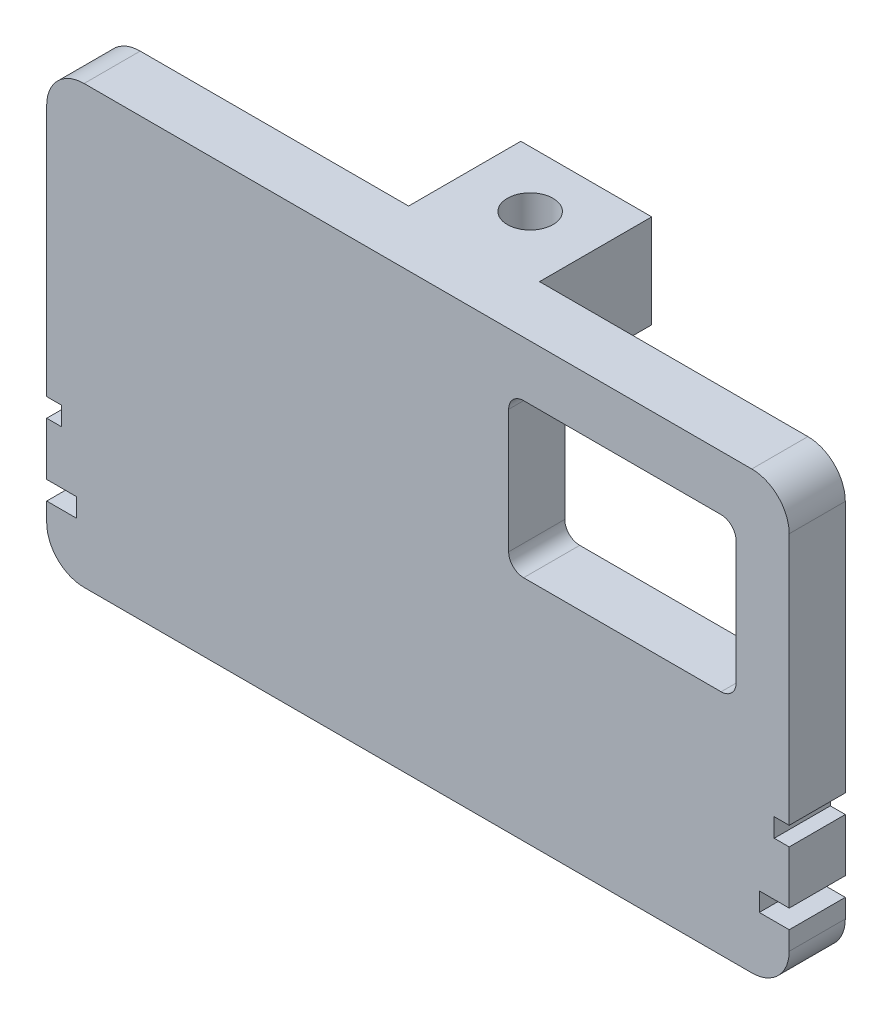
SolidWorks part; units mm, degrees
ref_plane "Front Plane" through (0, 0, 0) normal (0, 0, 1) x (1, 0, 0)
ref_plane "Top Plane" through (0, 0, 0) normal (0, 1, 0) x (1, 0, 0)
ref_plane "Right Plane" through (0, 0, 0) normal (1, 0, 0) x (0, 0, -1)
sketch "Sketch1" plane through (0, 0, 0) normal (0, 0, 1) x (1, 0, 0)
  line L0 (34.5888, 28.0084) -> (-10.7502, 28.0084) construction
  line L1 (34.5888, -1.6266) -> (-10.7502, -1.6266) construction
  line L2 (37.1288, 0.9134) -> (37.1288, 2.1834) construction
  line L3 (37.1288, 0.9134) -> (37.1288, 2.1834)
  line L4 (37.1288, 2.1834) -> (35.0968, 2.1834)
  line L5 (35.0968, 2.1834) -> (35.0968, 3.4534)
  line L6 (35.0968, 3.4534) -> (37.1288, 3.4534)
  line L7 (37.1288, 3.4534) -> (37.1288, 7.0534)
  line L8 (37.1288, 7.0534) -> (36.1128, 7.0534)
  line L9 (36.1128, 7.0534) -> (36.1128, 8.3234)
  line L10 (36.1128, 8.3234) -> (37.1288, 8.3234)
  line L11 (37.1288, 8.3234) -> (37.1288, 25.4684)
  line L12 (34.5888, -1.6266) -> (-10.7502, -1.6266)
  line L13 (-13.2902, 0.9134) -> (-13.2902, 2.1834)
  line L14 (-13.2902, 2.1834) -> (-11.2582, 2.1834)
  line L15 (-11.2582, 2.1834) -> (-11.2582, 3.4534)
  line L16 (-11.2582, 3.4534) -> (-13.2902, 3.4534)
  line L17 (-13.2902, 3.4534) -> (-13.2902, 7.0534) construction
  line L18 (-11.2582, 3.4534) -> (-13.2902, 3.4534) construction
  line L19 (-13.2902, 3.4534) -> (-13.2902, 7.0534)
  line L20 (-13.2902, 7.0534) -> (-12.2742, 7.0534)
  line L21 (-12.2742, 7.0534) -> (-12.2742, 8.3234)
  line L22 (-12.2742, 8.3234) -> (-13.2902, 8.3234)
  line L23 (-13.2902, 8.3234) -> (-13.2902, 25.4684)
  line L24 (-10.7502, 28.0084) -> (34.5888, 28.0084)
  line L25 (21.8888, 20.4696) -> (29.712, 20.4696) construction
  line L26 (32.506, 24.2796) -> (19.0948, 24.2796)
  line L27 (33.522, 23.2636) -> (33.522, 14.8816)
  line L28 (32.506, 13.8656) -> (19.0948, 13.8656)
  line L29 (18.0788, 23.2636) -> (18.0788, 14.8816)
  line L30 (21.8888, 17.6756) -> (29.712, 17.6756) construction
  line L31 (29.712, 20.4696) -> (29.712, 17.6756) construction
  line L32 (21.8888, 20.4696) -> (21.8888, 17.6756) construction
  arc A0 (-13.2902, 25.4684) -> (-10.7502, 28.0084) centre (-10.7502, 25.4684) cw
  arc A1 (34.5888, 28.0084) -> (37.1288, 25.4684) centre (34.5888, 25.4684) cw
  arc A2 (37.1288, 25.4684) -> (34.5888, 28.0084) centre (34.5888, 25.4684) ccw construction
  arc A3 (-13.2902, 0.9134) -> (-10.7502, -1.6266) centre (-10.7502, 0.9134) ccw
  arc A4 (34.5888, -1.6266) -> (37.1288, 0.9134) centre (34.5888, 0.9134) ccw
  arc A5 (19.0948, 13.8656) -> (18.0788, 14.8816) centre (19.0948, 14.8816) cw
  arc A6 (33.522, 14.8816) -> (32.506, 13.8656) centre (32.506, 14.8816) cw
  arc A7 (32.506, 24.2796) -> (33.522, 23.2636) centre (32.506, 23.2636) cw
  arc A8 (19.0948, 24.2796) -> (18.0788, 23.2636) centre (19.0948, 23.2636) ccw
  dimension "D5" = 1.016
  dimension "D1" = 3.81
  dimension "D2" = 3.81
  dimension "D3" = 3.81
  dimension "D4" = 3.81
extrude "Boss-Extrude1" add sketch "Sketch1" against normal blind 3.81
sketch "Sketch2" plane through (0, 0, -3.81) normal (0, 0, -1) x (-1, 0, 0)
  line L0 (-34.5888, 28.0084) -> (10.7502, 28.0084) construction
  line L2 (-16.3643, 28.0084) -> (-7.4743, 28.0084)
  line L3 (-16.3643, 28.0084) -> (-16.3643, 21.6584)
  line L4 (-16.3643, 21.6584) -> (-7.4743, 21.6584)
  line L5 (-7.4743, 28.0084) -> (-7.4743, 21.6584)
  point P0 (-11.9193, 28.0084)
  point P1 (-16.3643, 28.0084)
  dimension "D1" = 4.445
  dimension "D2" = 8.89
  dimension "D3" = 6.35
extrude "Boss-Extrude2" add sketch "Sketch2" along normal blind 7.62
sketch "Sketch3" plane through (0, 28.0084, 0) normal (0, 1, 0) x (1, 0, 0)
  line L0 (7.4743, 3.81) -> (16.3643, 11.43)
  circle A0 centre (11.9193, 7.62) radius 1.55
  dimension "D1" = 3.1
extrude "Cut-Extrude1" cut sketch "Sketch3" against normal blind 7.62 contours L0 A0 | L0 A0
sketch "Sketch4" plane through (0, 0, -11.43) normal (0, 0, -1) x (-1, 0, 0)
  line L0 (-7.4743, 24.8334) -> (-16.3643, 24.8334)
  line L1 (-7.4743, 21.6584) -> (-7.4743, 28.0084) construction
  line L2 (-16.3643, 28.0084) -> (-16.3643, 21.6584) construction
  line L4 (-8.9193, 25.7589) -> (-14.9193, 25.7589)
  line L5 (-8.9193, 25.7589) -> (-8.9193, 23.1589)
  line L6 (-8.9193, 23.1589) -> (-14.9193, 23.1589)
  line L7 (-14.9193, 25.7589) -> (-14.9193, 23.1589)
  point P10 (-11.9193, 25.7589)
  point P11 (-11.9193, 24.8334)
  dimension "D1" = 0
  dimension "D2" = 2.6
  dimension "D3" = 6
extrude "Cut-Extrude2" cut sketch "Sketch4" against normal blind 7.62 contours L0 L7 L6 L5 | L4 L7 L0 L5
